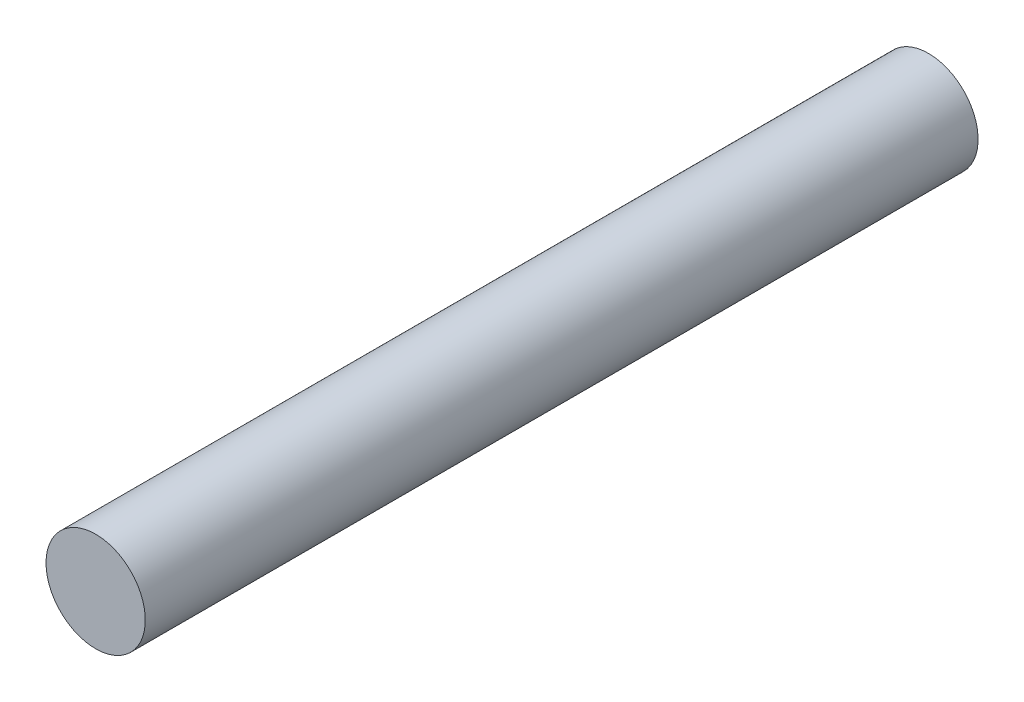
SolidWorks part; units mm, degrees
ref_plane "前视基准面" through (0, 0, 0) normal (0, 0, 1) x (1, 0, 0)
ref_plane "上视基准面" through (0, 0, 0) normal (0, 1, 0) x (1, 0, 0)
ref_plane "右视基准面" through (0, 0, 0) normal (1, 0, 0) x (0, 0, -1)
sketch "草图1" plane through (0, 0, 0) normal (0, 0, 1) x (1, 0, 0)
  circle A0 centre (0, 0) radius 3.1
extrude "凸台-拉伸1" add sketch "草图1" along normal blind 52
